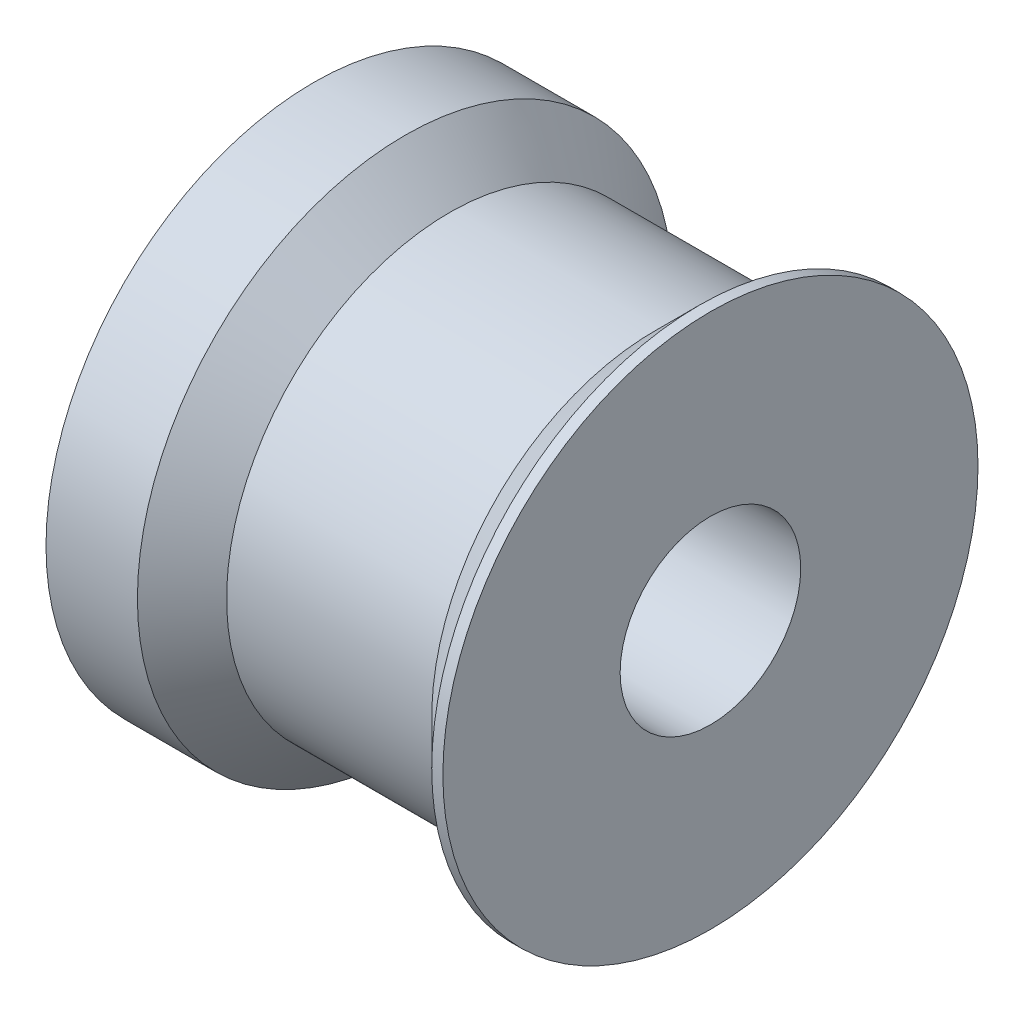
SolidWorks part; units mm, degrees
ref_plane "Front Plane" through (0, 0, 0) normal (0, 0, 1) x (1, 0, 0)
ref_plane "Top Plane" through (0, 0, 0) normal (0, 1, 0) x (1, 0, 0)
ref_plane "Right Plane" through (0, 0, 0) normal (1, 0, 0) x (0, 0, -1)
sketch "Sketch2" plane through (0, 0, 0) normal (0, 1, 0) x (1, 0, 0)
  line L0 (-7.1, 12) -> (-6.6, 12)
  line L1 (-6.6, 12) -> (-4.6, 10)
  line L2 (-4.6, 10) -> (4.6, 10)
  line L3 (4.6, 10) -> (6.6, 12)
  line L4 (6.6, 12) -> (7.1, 12)
  line L5 (7.1, 12) -> (7.1, 0)
  line L6 (-7.1, 12) -> (-7.1, 0) construction
  line L7 (-54.6936, 0) -> (47.2254, 0) construction
  line L8 (0, -23.2469) -> (0, 34.557) construction
  line L9 (7.1, 0) -> (-7.1, 0)
  line L10 (-7.1, 12) -> (-7.7, 12)
  line L11 (-7.7, 12) -> (-7.7, 0)
  line L12 (-7.7, 0) -> (-7.1, 0)
  line L13 (-7.1, 0) -> (-7.7, 0)
  point P16 (0, 10)
  dimension "D1" = 12
  dimension "D2" = 2.5
  dimension "D3" = 9.2
  dimension "D4" = 10
  dimension "D5" = 0.6
revolve "Revolve1" add sketch "Sketch2" angle 360 about L9
sketch "Sketch3" plane through (-7.7, 0, 0) normal (-1, 0, 0) x (0, 0, 1)
  circle A0 centre (0, 0) radius 2
  dimension "D1" = 4
extrude "Cut-Extrude1" cut sketch "Sketch3" against normal up to surface (14.8 mm away) up to face at (7.1, 0, -12)
sketch "Sketch4" plane through (-7.7, 0, 0) normal (-1, 0, 0) x (0, 0, 1)
  circle A0 centre (0, 0) radius 4.05
  point P2 (0, -0.7579)
  point P3 (0, 0)
  dimension "D1" = 8.1
extrude "Cut-Extrude2" cut sketch "Sketch4" against normal up to surface (12.8 mm away) from offset 2 up to face at (7.1, 0, 2) offset against normal yes
sketch "Sketch5" plane through (-7.7, 0, 0) normal (-1, 0, 0) x (0, 0, 1)
  circle A3 centre (0, 0) radius 12
  circle A4 centre (0, 0) radius 12
  circle A6 centre (0, 0) radius 2
  circle A7 centre (0, 0) radius 2
  dimension "D1" = 0
  dimension "D2" = 0
extrude "Boss-Extrude1" add sketch "Sketch5" along normal blind 3
